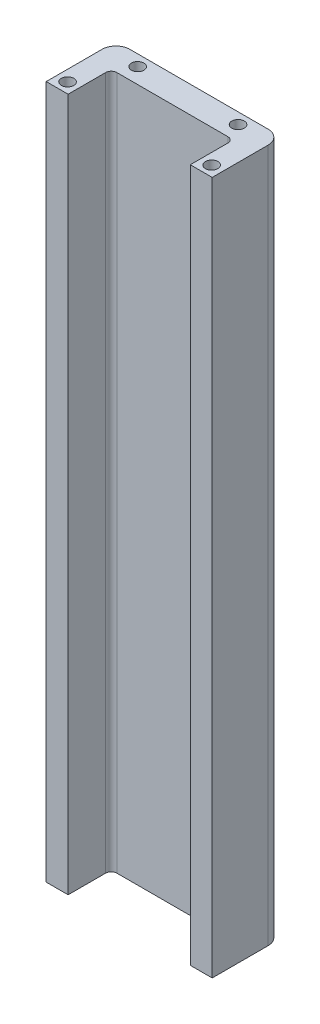
SolidWorks part; units mm, degrees
ref_plane "Front Plane" through (0, 0, 0) normal (0, 0, 1) x (1, 0, 0)
ref_plane "Top Plane" through (0, 0, 0) normal (0, 1, 0) x (1, 0, 0)
ref_plane "Right Plane" through (0, 0, 0) normal (1, 0, 0) x (0, 0, -1)
sketch "Sketch2" plane through (0, 0, 0) normal (0, 1, 0) x (1, 0, 0)
  line L0 (-22.025, -12.575) -> (-22.025, 0.975)
  line L1 (29.925, -12.575) -> (22.025, -12.575)
  line L2 (29.925, -12.575) -> (29.925, 7.575)
  line L3 (24.925, 12.575) -> (-24.925, 12.575)
  line L4 (-29.925, -12.575) -> (-29.925, 7.575)
  line L5 (29.925, -12.575) -> (-29.925, 12.575) construction
  line L6 (29.925, 12.575) -> (-29.925, -12.575) construction
  line L7 (-20.025, 2.975) -> (20.025, 2.975)
  line L8 (22.025, 0.975) -> (22.025, -12.575)
  line L9 (-22.025, -12.575) -> (-29.925, -12.575)
  line L10 (0, 0) -> (0, 27.1158) construction
  line L11 (25.975, -12.575) -> (25.975, 1.6823) construction
  arc A0 (24.925, 12.575) -> (29.925, 7.575) centre (24.925, 7.575) cw
  arc A1 (-24.925, 12.575) -> (-29.925, 7.575) centre (-24.925, 7.575) ccw
  arc A2 (-20.025, 2.975) -> (-22.025, 0.975) centre (-20.025, 0.975) ccw
  arc A3 (22.025, 0.975) -> (20.025, 2.975) centre (20.025, 0.975) ccw
  circle A4 centre (18.1, 8.575) radius 2.25
  circle A5 centre (25.975, -8.825) radius 2.25
  circle A6 centre (-25.975, -8.825) radius 2.25
  circle A7 centre (-18.1, 8.575) radius 2.25
  point P0 (0, 0)
  point P28 (0, 0)
  dimension "D5" = 2
  dimension "D6" = 5
  dimension "D7" = 4.5
  dimension "D8" = 18.1
  dimension "D1" = 25.15
  dimension "D2" = 59.85
  dimension "D3" = 9.6
  dimension "D4" = 7.9
  dimension "D9" = 4
  dimension "D10" = 3.75
extrude "Boss-Extrude1" add sketch "Sketch2" against normal blind 250
